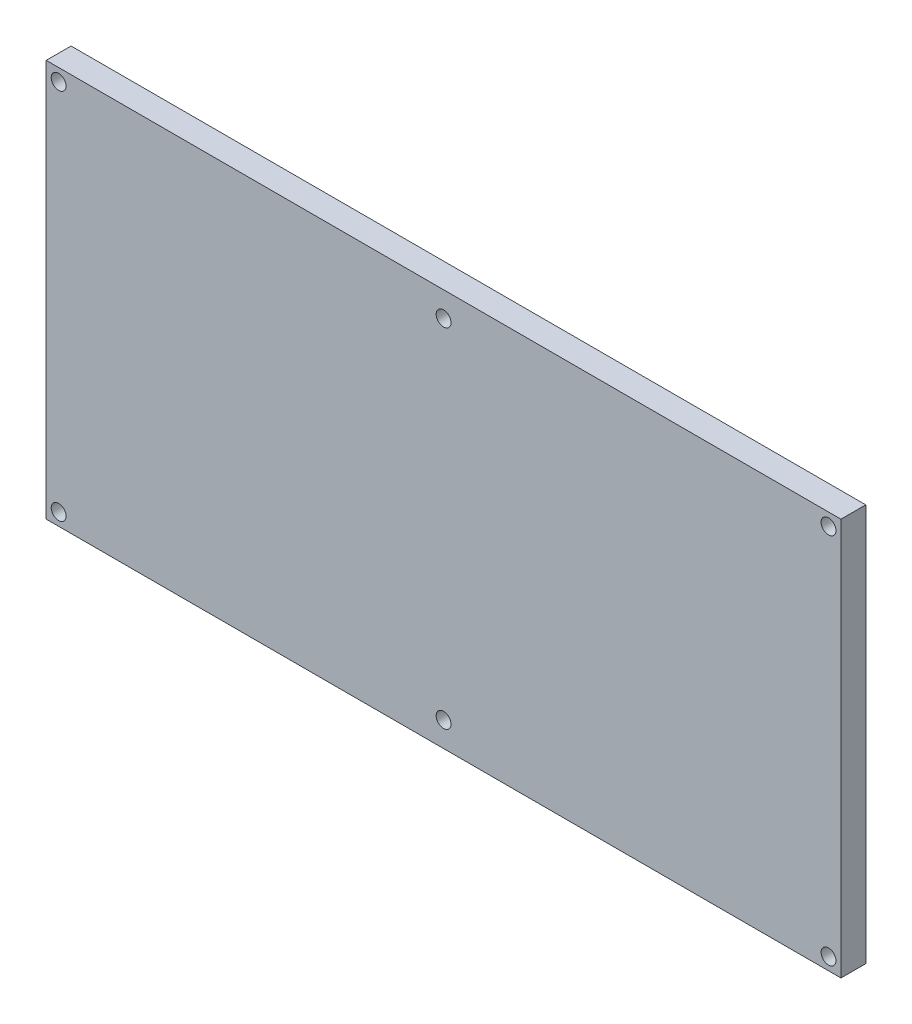
SolidWorks part; units mm, degrees
material "Acrylic (Medium-high impact)"
ref_plane "Front Plane" through (0, 0, 0) normal (0, 0, 1) x (1, 0, 0)
ref_plane "Top Plane" through (0, 0, 0) normal (0, 1, 0) x (1, 0, 0)
ref_plane "Right Plane" through (0, 0, 0) normal (1, 0, 0) x (0, 0, -1)
sketch "Sketch1" plane through (0, 0, 0) normal (0, 0, 1) x (1, 0, 0)
  line L1 (0, 0) -> (203.2, 0)
  line L2 (0, 0) -> (0, 101.6)
  line L3 (0, 101.6) -> (203.2, 101.6)
  line L4 (203.2, 0) -> (203.2, 101.6)
  dimension "D1" = 203.2
  dimension "D2" = 101.6
extrude "Boss-Extrude1" add sketch "Sketch1" along normal blind 6.35
sketch "Sketch2" plane through (0, 0, 6.35) normal (0, 0, 1) x (1, 0, 0)
  line L0 (203.2, 101.6) -> (0, 101.6) construction
  line L1 (0, 0) -> (203.2, 0) construction
  line L2 (0, 101.6) -> (0, 0) construction
  line L3 (101.6, 101.6) -> (101.6, 0) construction
  line L4 (0, 0) -> (203.2, 0) construction
  point P0 (3.175, 98.425)
  point P1 (3.175, 3.175)
  point P2 (200.025, 3.175)
  point P3 (200.025, 98.425)
  point P6 (101.6, 95.25)
  point P7 (101.6, 6.35)
  dimension "D1" = 3.175
  dimension "D2" = 3.175
  dimension "D3" = 3.175
  dimension "D4" = 6.35
  dimension "D5" = 6.35
hole_wizard "#6 Clearance Hole1" positions "Sketch5" profile "Sketch6" hole size "#6" standard "ANSI Inch" end condition through all
sketch "Sketch5" plane through (0, 0, 6.35) normal (0, 0, 1) x (1, 0, 0)
  point P0 (3.175, 3.175)
  point P3 (3.175, 98.425)
  point P6 (200.025, 98.425)
  point P9 (200.025, 3.175)
  point P13 (101.6, 95.25)
  point P16 (101.6, 6.35)
sketch "Sketch6" plane through (3.175, 3.175, 6.35) normal (1, 0, 0) x (0, -1, 0)
  line L0 (0, 0) -> (0, 6.35)
  line L1 (0, 6.35) -> (1.8986, 6.35)
  line L2 (1.8986, 6.35) -> (1.8986, 0)
  line L5 (1.8986, 0) -> (0, 0)
  line L11 (0, -6.35) -> (0, 107.95) construction
  dimension "Thru Hole Dia." = 3.7973
  dimension "Thru Hole Depth" = 6.35
